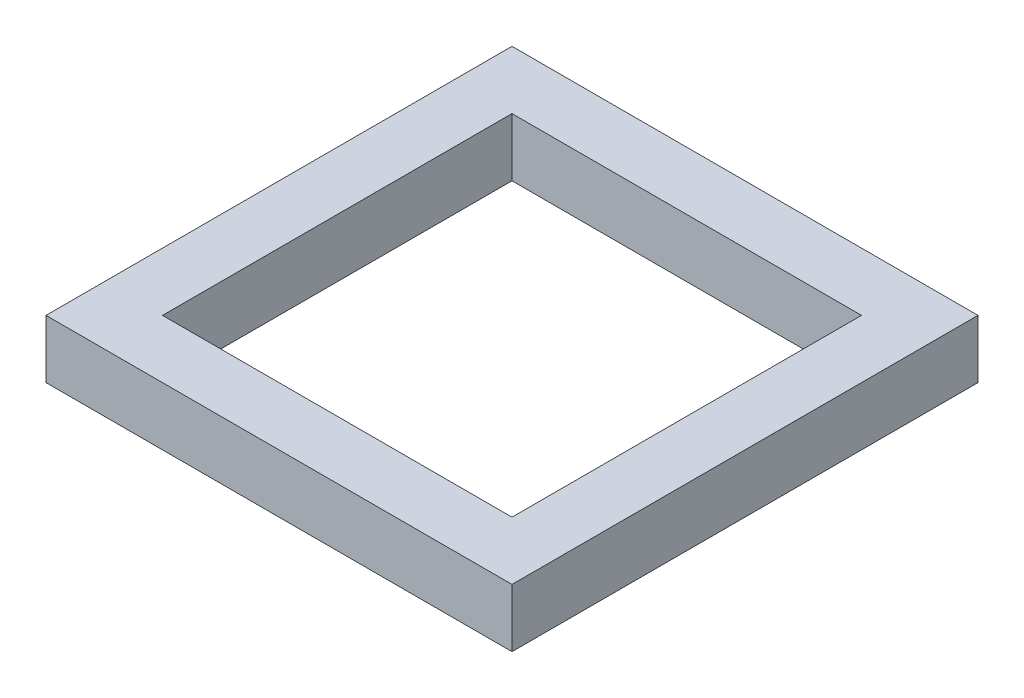
SolidWorks part; units mm, degrees
ref_plane "Front Plane" through (0, 0, 0) normal (0, 0, 1) x (1, 0, 0)
ref_plane "Top Plane" through (0, 0, 0) normal (0, 1, 0) x (1, 0, 0)
ref_plane "Right Plane" through (0, 0, 0) normal (1, 0, 0) x (0, 0, -1)
ref_plane "Drive_Base" through (0, 2.54, 0) normal (0, 1, 0) x (1, 0, 0)
ref_plane "Electricals" through (0, 53.34, 0) normal (0, 1, 0) x (1, 0, 0)
ref_plane "Shooter" through (0, 104.14, 0) normal (0, 1, 0) x (1, 0, 0)
sketch "KOBE Perimeter" plane through (0, 2.54, 0) normal (0, 1, 0) x (1, 0, 0)
  line L1 (-150, -150) -> (150, -150)
  line L2 (-150, -150) -> (-150, 150)
  line L3 (-150, 150) -> (150, 150)
  line L4 (150, -150) -> (150, 150)
  line L5 (-150, -150) -> (150, 150) construction
  line L6 (-150, 150) -> (150, -150) construction
  point P0 (0, 0)
  dimension "D1" = 300
  dimension "D2" = 300
ref_plane "Bumper_Base" through (0, 13, 0) normal (0, 1, 0) x (1, 0, 0)
ref_plane "Bumper_Boss" through (0, 63, 0) normal (0, 1, 0) x (1, 0, 0)
sketch "Bumper_Perimeter" plane through (0, 13, 0) normal (0, 1, 0) x (1, 0, 0)
  line L0 (-150, 0) -> (-200, 0) construction
  line L1 (-150, -150) -> (150, -150)
  line L2 (-150, -150) -> (-150, 150)
  line L3 (-150, 150) -> (150, 150)
  line L4 (150, -150) -> (150, 150)
  line L5 (-150, -150) -> (150, 150) construction
  line L6 (-150, 150) -> (150, -150) construction
  line L7 (-200, -200) -> (200, -200)
  line L8 (-200, -200) -> (-200, 200)
  line L9 (-200, 200) -> (200, 200)
  line L10 (200, -200) -> (200, 200)
  line L11 (-200, -200) -> (200, 200) construction
  line L12 (-200, 200) -> (200, -200) construction
  line L13 (0, 150) -> (0, 200) construction
  point P0 (0, 0)
  point P7 (0, 0)
  dimension "D1" = 50
  dimension "D2" = 50
extrude "Bumper_Space" add sketch "Bumper_Perimeter" along normal up to surface (50 mm away) up to plane "Bumper_Boss"
sketch "mounting_holes" plane through (0, 2.54, 0) normal (0, 1, 0) x (1, 0, 0)
  line L0 (0, 150) -> (0, 50150) construction
  line L1 (-150, 150) -> (150, 150) construction
  line L2 (-141.6688, 166.3182) -> (-141.6688, 50166.3182) construction
  line L3 (0, 0) -> (-50000, 0) construction
  line L4 (-150, 150) -> (-150, -150) construction
  line L5 (-32.0192, 32.0192) -> (-35292.0127, 35292.0127) construction
  line L7 (-61.8825, -61.8825) -> (35293.4566, 35293.4566) construction
  circle A0 centre (0, 141.6688) radius 2.0828
  circle A1 centre (38.1, 141.6688) radius 2.0828
  circle A2 centre (76.2, 141.6688) radius 2.0828
  circle A3 centre (-38.1, 141.6688) radius 2.0828
  circle A4 centre (-76.2, 141.6688) radius 2.0828
  circle A5 centre (76.2, -141.6688) radius 2.0828
  circle A6 centre (38.1, -141.6688) radius 2.0828
  circle A7 centre (0, -141.6688) radius 2.0828
  circle A8 centre (-38.1, -141.6688) radius 2.0828
  circle A9 centre (-76.2, -141.6688) radius 2.0828
  circle A10 centre (-141.6688, 99.2) radius 2.0828
  circle A11 centre (-141.6688, 61.1) radius 2.0828
  circle A12 centre (141.6688, 61.1) radius 2.0828
  circle A13 centre (141.6688, 99.2) radius 2.0828
  circle A14 centre (141.6688, -99.2) radius 2.0828
  circle A15 centre (141.6688, -61.1) radius 2.0828
  circle A16 centre (-141.6688, -61.1) radius 2.0828
  circle A17 centre (-141.6688, -99.2) radius 2.0828
  circle A18 centre (-78.158, 78.158) radius 2.0828
  circle A19 centre (78.158, 78.158) radius 2.0828
  circle A20 centre (78.158, -78.158) radius 2.0828
  circle A21 centre (-78.158, -78.158) radius 2.0828
  point P4 (0, 150)
  point P8 (0, 141.6688)
  point P55 (0, 0)
  point P57 (-73.0966, 83.604)
  dimension "D1" = 4.1656
  dimension "D7" = 4.1656
  dimension "D11" = 4.1656
  dimension "D4" = 8.3312
  dimension "D5" = 8.3312
  dimension "D6" = 38.1
  dimension "D8" = 50.8
  dimension "D9" = 38.1
  dimension "D10" = 38.1
  dimension "D12" = 101.6
  dimension "D2" = 3
  dimension "D3" = 3
